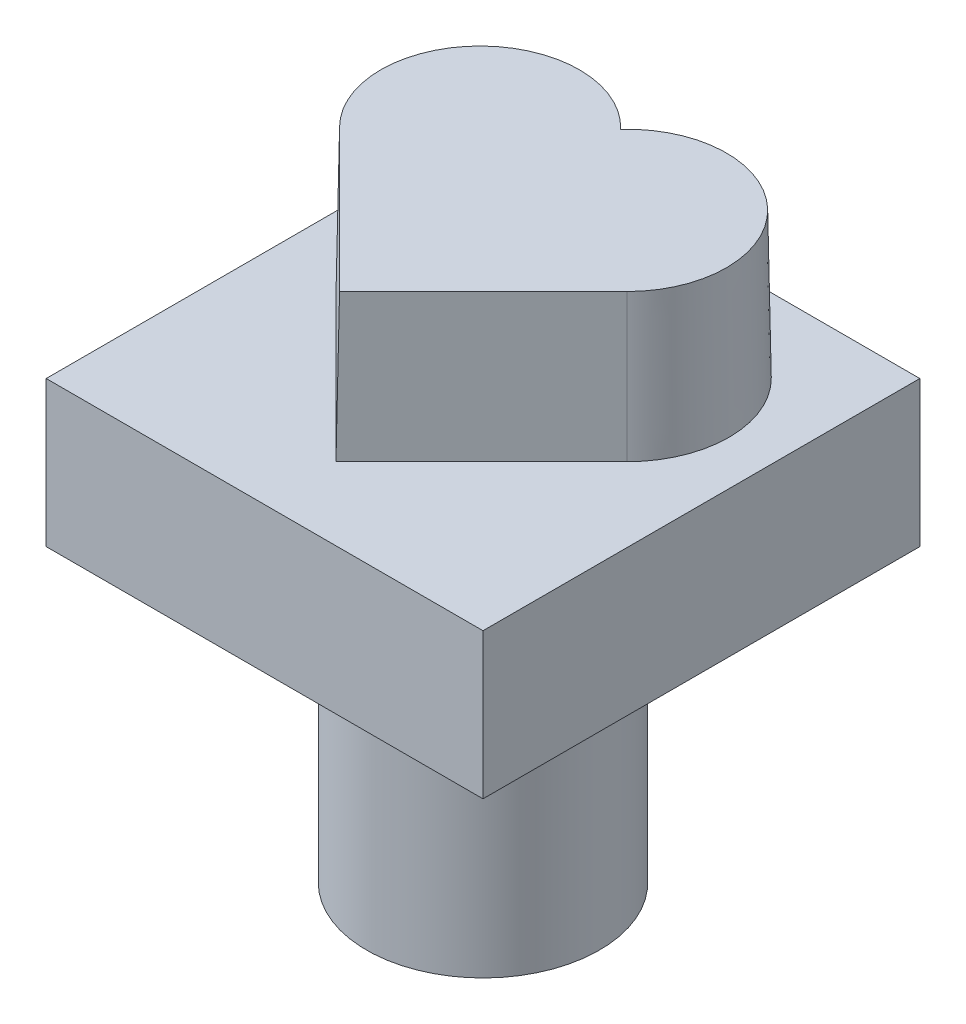
SolidWorks part; units mm, degrees
ref_plane "Front Plane" through (0, 0, 0) normal (0, 0, 1) x (1, 0, 0)
ref_plane "Top Plane" through (0, 0, 0) normal (0, 1, 0) x (1, 0, 0)
ref_plane "Right Plane" through (0, 0, 0) normal (1, 0, 0) x (0, 0, -1)
sketch "Sketch1" plane through (0, 0, 0) normal (0, 1, 0) x (1, 0, 0)
  line L1 (7.5, -7.5) -> (-7.5, -7.5)
  line L2 (7.5, -7.5) -> (7.5, 7.5)
  line L3 (7.5, 7.5) -> (-7.5, 7.5)
  line L4 (-7.5, -7.5) -> (-7.5, 7.5)
  line L5 (7.5, -7.5) -> (-7.5, 7.5) construction
  line L6 (7.5, 7.5) -> (-7.5, -7.5) construction
  point P0 (0, 0)
  dimension "D1" = 15
  dimension "D2" = 15
extrude "Boss-Extrude1" add sketch "Sketch1" along normal blind 5
sketch "Sketch2" plane through (0, 5, 0) normal (0, 1, 0) x (1, 0, 0)
  line L3 (-4.9995, -0.0497) -> (-0.0497, -4.9995)
  line L4 (-0.0497, -4.9995) -> (4.9497, 0)
  arc A0 (-0.0492, 4.8995) -> (-4.9995, -0.0497) centre (-2.5246, 2.4251) ccw
  arc A1 (4.9497, 0) -> (-0.0492, 4.8995) centre (2.4749, 2.4749) ccw
  dimension "D1" = 3.5
  dimension "D2" = 3.5
extrude "Boss-Extrude2" add sketch "Sketch2" along normal blind 5 draft 1
sketch "Sketch3" plane through (0, 0, 0) normal (0, -1, 0) x (1, 0, 0)
  circle A0 centre (0, 0) radius 4
  dimension "D1" = 8
extrude "Boss-Extrude3" add sketch "Sketch3" along normal blind 10
equation "\"Connector_Dia\"= 8mm"
equation "\"Connector_height\"= 10mm"
equation "\"Base_side\"= 15mm"
equation "\"Base_thickness\"= 5mm"
equation "\"D1@Boss-Extrude3\"=\"Connector_height\""
equation "\"D1@Sketch3\"=\"Connector_Dia\""
equation "\"D1@Boss-Extrude1\"=\"Base_thickness\""
equation "\"D2@Sketch1\"=\"Base_side\""
equation "\"D1@Sketch1\"=\"Base_side\""
equation "\"Indenter_height\" = 5mm"
equation "\"draft_angle\" = 0deg"
equation "\"D3@Boss-Extrude2\"=\"draft_angle\""
equation "\"D1@Boss-Extrude2\"=\"Indenter_height\""
